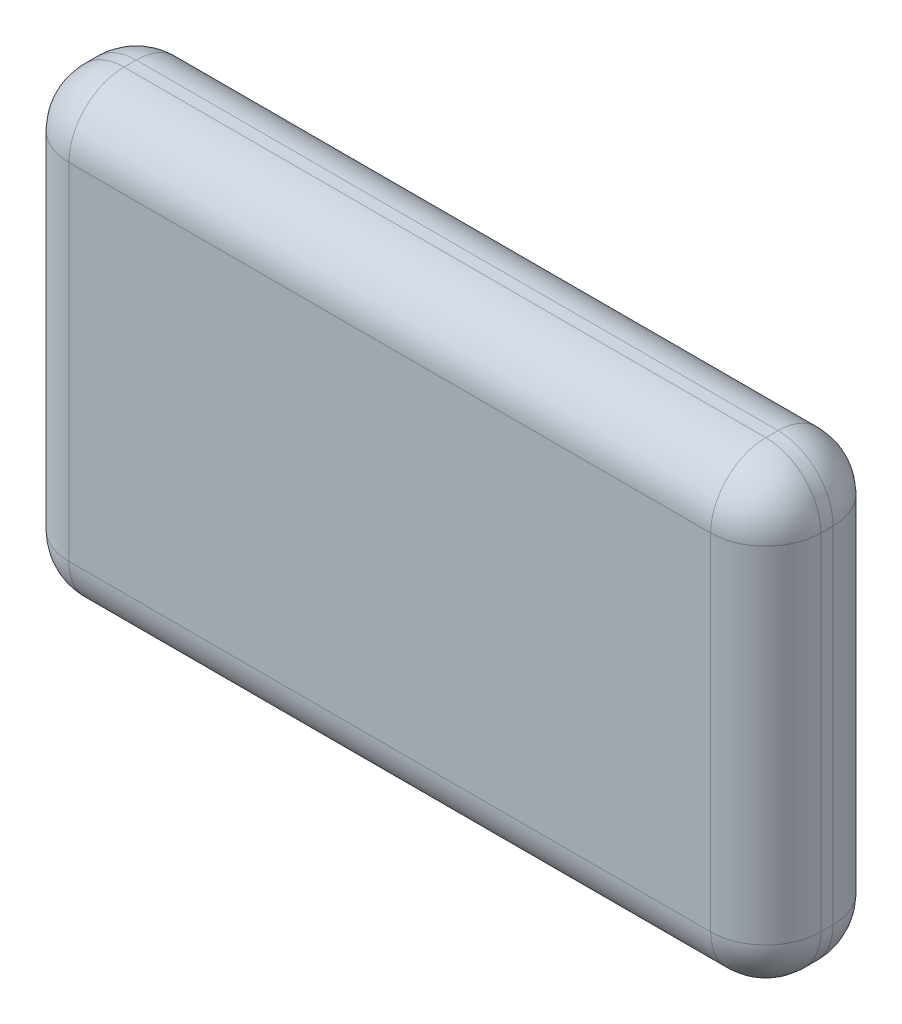
SolidWorks part; units mm, degrees
ref_plane "Front Plane" through (0, 0, 0) normal (0, 0, 1) x (1, 0, 0)
ref_plane "Top Plane" through (0, 0, 0) normal (0, 1, 0) x (1, 0, 0)
ref_plane "Right Plane" through (0, 0, 0) normal (1, 0, 0) x (0, 0, -1)
sketch "Sketch1" plane through (0, 0, 0) normal (0, 0, 1) x (1, 0, 0)
  line L1 (-158.5992, 357.136) -> (455.7997, 357.136)
  line L2 (-158.5992, 357.136) -> (-158.5992, -15.1061)
  line L3 (-158.5992, -15.1061) -> (455.7997, -15.1061)
  line L4 (455.7997, 357.136) -> (455.7997, -15.1061)
extrude "Boss-Extrude1" add sketch "Sketch1" along normal blind 100
fillet "Fillet1" radius 45 12 edges at (148.6002, 357.136, 100) (455.7997, 171.015, 100) (148.6002, -15.1061, 100) (-158.5992, 171.015, 100) (148.6002, -15.1061, 0) (455.7997, 171.015, 0) (148.6002, 357.136, 0) (-158.5992, 171.015, 0) (-158.5992, -15.1061, 50) (-158.5992, 357.136, 50) (455.7997, 357.136, 50) (455.7997, -15.1061, 50)
